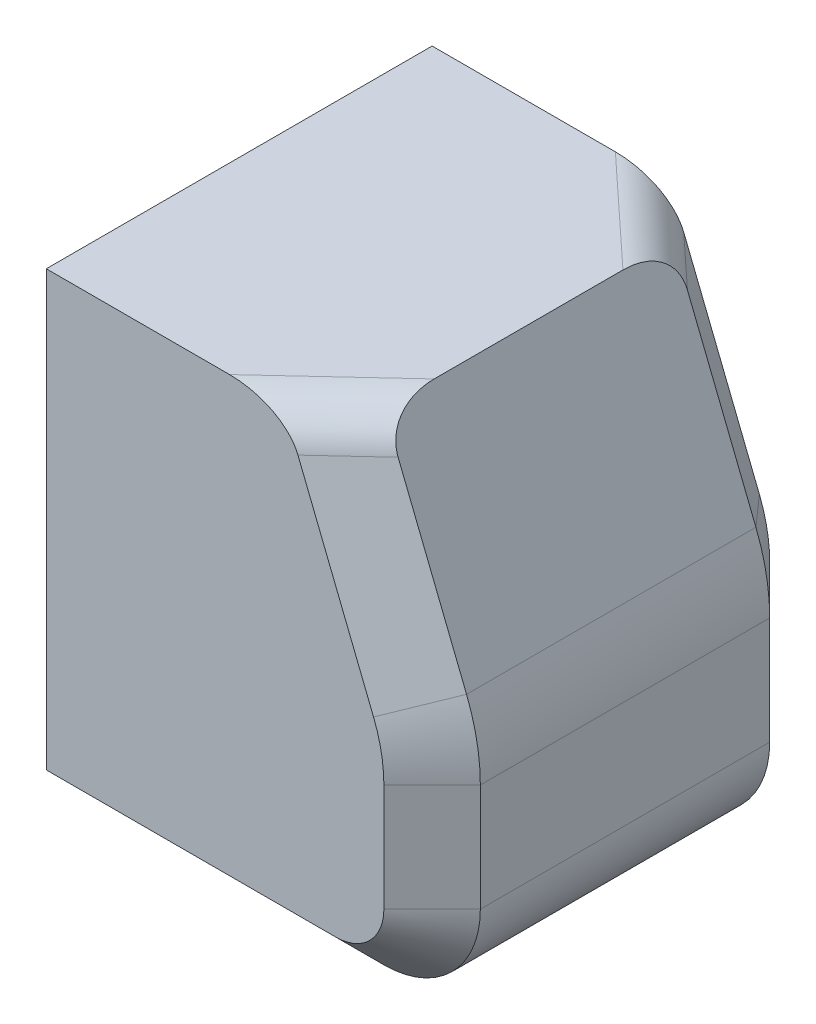
SolidWorks part; units mm, degrees
ref_plane "Front Plane" through (0, 0, 0) normal (0, 0, 1) x (1, 0, 0)
ref_plane "Top Plane" through (0, 0, 0) normal (0, 1, 0) x (1, 0, 0)
ref_plane "Right Plane" through (0, 0, 0) normal (1, 0, 0) x (0, 0, -1)
sketch "Sketch2" plane through (0, 0, 0) normal (0, 0, 1) x (1, 0, 0)
  line L0 (0, 0) -> (0, 50)
  line L1 (0, 50) -> (30, 50)
  line L2 (30, 50) -> (38.5695, 28.5762)
  line L3 (40, 21.1484) -> (40, 10)
  line L4 (30, 0) -> (0, 0)
  arc A0 (38.5695, 28.5762) -> (40, 21.1484) centre (20, 21.1484) cw
  arc A1 (40, 10) -> (30, 0) centre (30, 10) cw
  point P8 (40, 25)
  point P11 (40, 0)
  dimension "D5" = 20
  dimension "D6" = 10
  dimension "D1" = 50
  dimension "D2" = 40
  dimension "D3" = 30
  dimension "D4" = 25
extrude "Boss-Extrude2" add sketch "Sketch2" along normal blind 40
chamfer "Chamfer2" distance 5 angle 45 10 edges at (40, 15.5742, 0) (39.6391, 24.9305, 0) (34.2848, 39.2881, 0) (40, 15.5742, 40) (39.6391, 24.9305, 40) (34.2848, 39.2881, 40) (15, 0, 0) (15, 0, 40) (37.0711, 2.9289, 0) (37.0711, 2.9289, 40)
fillet "Fillet2" radius 5 2 edges at (27.3074, 50, 2.5) (27.3074, 50, 37.5)
